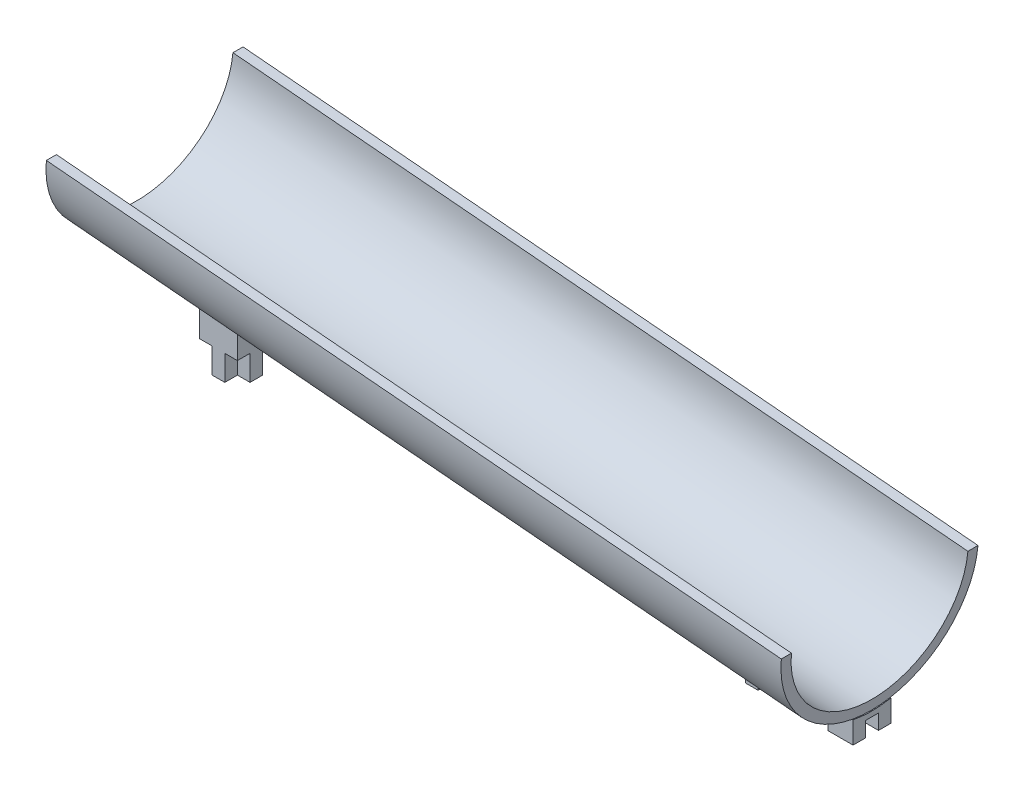
SolidWorks part; units mm, degrees
ref_plane "Front Plane" through (0, 0, 0) normal (0, 0, 1) x (1, 0, 0)
ref_plane "Top Plane" through (0, 0, 0) normal (0, 1, 0) x (1, 0, 0)
ref_plane "Right Plane" through (0, 0, 0) normal (1, 0, 0) x (0, 0, -1)
sketch "Sketch17" plane through (0, 0, 0) normal (0, 0, 1) x (1, 0, 0)
  line L0 (-56.9422, 0) -> (-56.9422, 25.5) construction
  line L1 (55, 0) -> (-55, 0) construction
  line L2 (-56.9422, 25.5) -> (234.5241, 0)
  line L3 (234.5241, 0) -> (-56.9422, 0) construction
  dimension "D1" = 25.5
  dimension "D2" = 5
sweep "Sweep2" add path "Sketch17" circular profile diameter 78 parameters "D3"=78
sketch "Sketch25" plane through (232.7426, -20.3623, 0) normal (0.9962, -0.0872, 0) x (0, 0, -1)
  line L2 (40.3774, 20.4401) -> (40.3774, 67.1844)
  line L3 (40.3774, 67.1844) -> (-52.3338, 67.1844)
  line L4 (-52.3338, 67.1844) -> (-52.3338, 20.4401)
  line L6 (-35, 20.4401) -> (-52.3338, 20.4401)
  line L7 (35, 20.4401) -> (40.3774, 20.4401)
  arc A0 (-35, 20.4401) -> (35, 20.4401) centre (0, 20.4401) ccw
  dimension "D1" = 35
extrude "Cut-Extrude5" cut sketch "Sketch25" against normal blind 400
sketch "Sketch28" plane through (0, 0, 0) normal (0, 0, 1) x (1, 0, 0)
  line L0 (-60.167, -11.3592) -> (231.2993, -36.8592) construction
  line L1 (231.2993, -36.8592) -> (-60.167, -36.8592) construction
  line L2 (-60.167, -36.8592) -> (-60.167, -11.3592) construction
  line L3 (-60.167, -36.8592) -> (-20.167, -36.8592) construction
  line L4 (231.2993, -36.8592) -> (191.2993, -36.8592) construction
  line L5 (234.5241, 0) -> (234.5241, -68) construction
  line L6 (234.5241, -68) -> (-60.167, -68) construction
  line L7 (-60.167, -68) -> (-60.167, -11.3592) construction
  line L8 (231.125, -38.8516) -> (234.5241, 0) construction
  line L9 (55, 0) -> (-55, 0) construction
  line L10 (191.2993, -36.8592) -> (191.2993, -68) construction
  line L11 (-20.167, -36.8592) -> (-20.167, -68) construction
  line L12 (231.2993, -46.8592) -> (-60.167, -46.8592)
  dimension "D1" = 90
  dimension "D2" = 40
  dimension "D3" = 40
  dimension "D4" = 68
  dimension "D5" = 90
  dimension "D6" = 10
  dimension "D7" = 21.1408
ref_plane "Plane1" through (0, -46.8592, 0) normal (0, 1, 0) x (1, 0, 0)
sketch "Sketch30" plane through (0, -46.8592, 0) normal (0, 1, 0) x (1, 0, 0)
  line L0 (-60.167, 0) -> (-20.167, 0) construction
  line L1 (-12.667, 7.5) -> (-27.667, 7.5)
  line L2 (-12.667, 7.5) -> (-12.667, -7.5)
  line L3 (-12.667, -7.5) -> (-27.667, -7.5)
  line L4 (-27.667, 7.5) -> (-27.667, -7.5)
  line L5 (-12.667, 7.5) -> (-27.667, -7.5) construction
  line L6 (-12.667, -7.5) -> (-27.667, 7.5) construction
  line L7 (-60.167, 0) -> (231.2993, 0) construction
  line L8 (231.2993, 0) -> (191.2993, 0) construction
  line L9 (198.7993, 7.5) -> (183.7993, 7.5)
  line L10 (198.7993, 7.5) -> (198.7993, -7.5)
  line L11 (198.7993, -7.5) -> (183.7993, -7.5)
  line L12 (183.7993, 7.5) -> (183.7993, -7.5)
  line L13 (198.7993, 7.5) -> (183.7993, -7.5) construction
  line L14 (198.7993, -7.5) -> (183.7993, 7.5) construction
  point P0 (-20.167, 0)
  point P9 (191.2993, 0)
  dimension "D1" = 15
extrude "Boss-Extrude2" add sketch "Sketch30" along normal up to surface (30.0674 mm away)
sketch "Sketch31" plane through (0, -46.8592, 0) normal (0, -1, 0) x (1, 0, 0)
  line L0 (-27.667, 2.5) -> (-22.667, 2.5)
  line L1 (-27.667, -7.5) -> (-27.667, 7.5) construction
  line L2 (-22.667, 2.5) -> (-22.667, 7.5)
  line L3 (-27.667, 7.5) -> (-12.667, 7.5) construction
  line L5 (-17.667, 7.5) -> (-17.667, 2.5)
  line L6 (-17.667, 2.5) -> (-12.667, 2.5)
  line L7 (-12.667, -7.5) -> (-12.667, 7.5) construction
  line L9 (-12.667, -2.5) -> (-17.667, -2.5)
  line L10 (-17.667, -2.5) -> (-17.667, -7.5)
  line L11 (-12.667, -7.5) -> (-27.667, -7.5) construction
  line L13 (-22.667, -7.5) -> (-22.667, -2.5)
  line L14 (-22.667, -2.5) -> (-27.667, -2.5)
  line L30 (183.7993, -2.5) -> (188.7993, -2.5)
  line L31 (183.7993, 7.5) -> (183.7993, -7.5) construction
  line L32 (188.7993, -2.5) -> (188.7993, -7.5)
  line L33 (183.7993, -7.5) -> (198.7993, -7.5) construction
  line L35 (193.7993, -7.5) -> (193.7993, -2.5)
  line L36 (193.7993, -2.5) -> (198.7993, -2.5)
  line L37 (198.7993, -7.5) -> (198.7993, 7.5) construction
  line L39 (198.7993, 7.5) -> (198.7993, -7.5) construction
  line L40 (198.7993, 2.5) -> (193.7993, 2.5)
  line L41 (193.7993, 2.5) -> (193.7993, 7.5)
  line L42 (198.7993, 7.5) -> (183.7993, 7.5) construction
  line L44 (183.7993, 7.5) -> (198.7993, 7.5) construction
  line L45 (188.7993, 7.5) -> (188.7993, 2.5)
  line L46 (188.7993, 2.5) -> (183.7993, 2.5)
  line L48 (-27.667, -2.5) -> (-27.667, -7.5)
  line L49 (-27.667, -7.5) -> (-22.667, -7.5)
  line L50 (-17.667, -7.5) -> (-12.667, -7.5)
  line L51 (-12.667, -7.5) -> (-12.667, -2.5)
  line L52 (-12.667, 2.5) -> (-12.667, 7.5)
  line L53 (-12.667, 7.5) -> (-17.667, 7.5)
  line L54 (-22.667, 7.5) -> (-27.667, 7.5)
  line L55 (-27.667, 7.5) -> (-27.667, 2.5)
  line L56 (183.7993, 7.5) -> (188.7993, 7.5)
  line L57 (183.7993, 2.5) -> (183.7993, 7.5)
  line L58 (193.7993, 7.5) -> (198.7993, 7.5)
  line L59 (198.7993, 7.5) -> (198.7993, 2.5)
  line L60 (198.7993, -2.5) -> (198.7993, -7.5)
  line L61 (198.7993, -7.5) -> (193.7993, -7.5)
  line L62 (188.7993, -7.5) -> (183.7993, -7.5)
  line L63 (183.7993, -7.5) -> (183.7993, -2.5)
  dimension "D1" = 5
  dimension "D2" = 5
extrude "Cut-Extrude6" cut sketch "Sketch31" against normal blind 10
sketch "Sketch38" plane through (0, -46.8592, 0) normal (0, 1, 0) x (1, 0, 0)
  line L0 (231.4736, 0) -> (231.4736, -7.5)
  line L1 (234.5241, 0) -> (-60.167, 0) construction
  line L2 (231.4736, -7.5) -> (221.4736, -7.5)
  line L3 (221.4736, -7.5) -> (221.4736, 7.5)
  line L4 (221.4736, 7.5) -> (231.4736, 7.5)
  line L5 (231.4736, 7.5) -> (231.4736, 0)
  ellipse E0 centre (234.5241, 0) end of major axis (234.5241, -35) minor radius 3.0505 (234.5241, 35) -> (234.5241, -35) ccw construction
  dimension "D1" = 15
  dimension "D2" = 10
extrude "Boss-Extrude3" add sketch "Sketch38" along normal up to surface (8.7078 mm away)
sketch "Sketch39" plane through (0, -46.8592, 0) normal (0, -1, 0) x (1, 0, 0)
  line L0 (231.4736, 0) -> (231.4736, 2.6)
  line L1 (231.4736, 7.5) -> (231.4736, -7.5) construction
  line L2 (231.4736, 2.6) -> (221.4736, 2.6)
  line L3 (221.4736, -7.5) -> (221.4736, 7.5) construction
  line L4 (221.4736, 2.6) -> (221.4736, -2.6)
  line L5 (221.4736, -2.6) -> (231.4736, -2.6)
  line L6 (231.4736, -2.6) -> (231.4736, 0)
  dimension "D1" = 5.2
extrude "Cut-Extrude7" cut sketch "Sketch39" against normal blind 6
